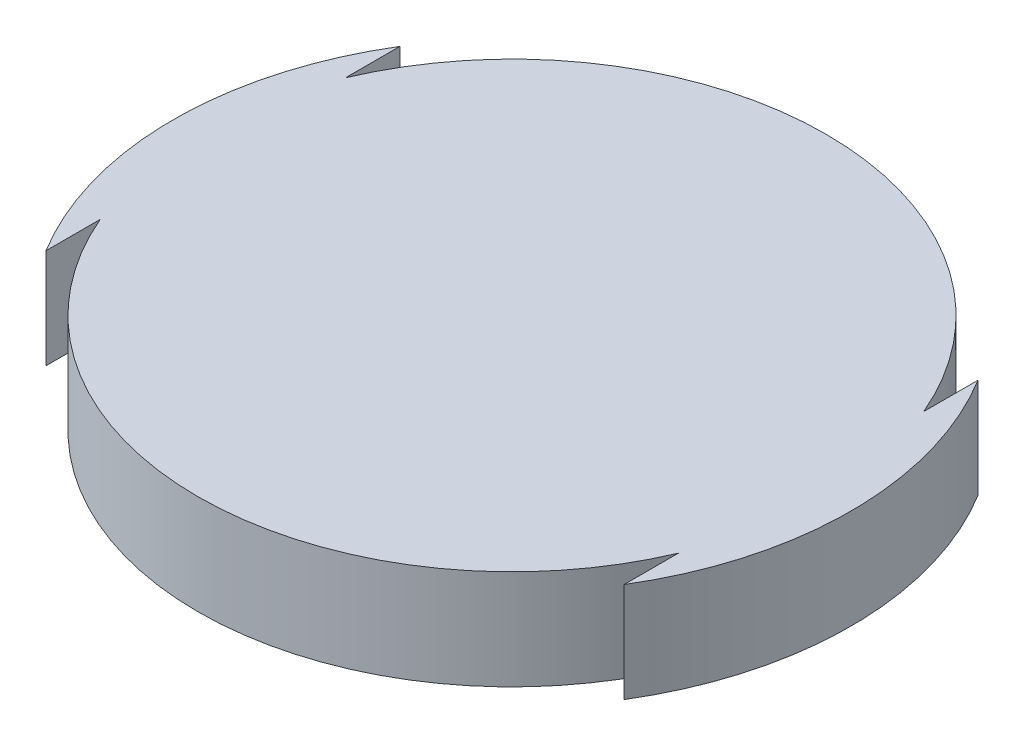
SolidWorks part; units mm, degrees
ref_plane "Front Plane" through (0, 0, 0) normal (0, 0, 1) x (1, 0, 0)
ref_plane "Top Plane" through (0, 0, 0) normal (0, 1, 0) x (1, 0, 0)
ref_plane "Right Plane" through (0, 0, 0) normal (1, 0, 0) x (0, 0, -1)
sketch "Sketch1" plane through (0, 0, 0) normal (0, 1, 0) x (1, 0, 0)
  circle A0 centre (0, 0) radius 68
  dimension "D1" = 136
extrude "Boss-Extrude1" add sketch "Sketch1" along normal blind 20
sketch "Sketch2" plane through (0, 20, 0) normal (0, 1, 0) x (1, 0, 0)
  line L0 (-58, -35.4965) -> (-58, -24.5967)
  line L1 (0, 37.0764) -> (0, -27.4787) construction
  line L2 (58, 35.4965) -> (58, 24.5967)
  line L3 (-58, 24.5967) -> (-58, 35.4965)
  line L4 (58, -24.5967) -> (58, -35.4965)
  arc A0 (-58, -24.5967) -> (58, -24.5967) centre (0, 0) ccw
  arc A1 (-58, -35.4965) -> (58, -35.4965) centre (0, 0) ccw
  circle A2 centre (0, 0) radius 68 construction
  arc A3 (58, 24.5967) -> (-58, 24.5967) centre (0, 0) ccw
  arc A4 (58, 35.4965) -> (-58, 35.4965) centre (0, 0) ccw
  dimension "D1" = 126
  dimension "D2" = 58
  dimension "D3" = 58
extrude "Cut-Extrude1" cut sketch "Sketch2" against normal up to surface (20 mm away) up to face at (0, 0, 68)
